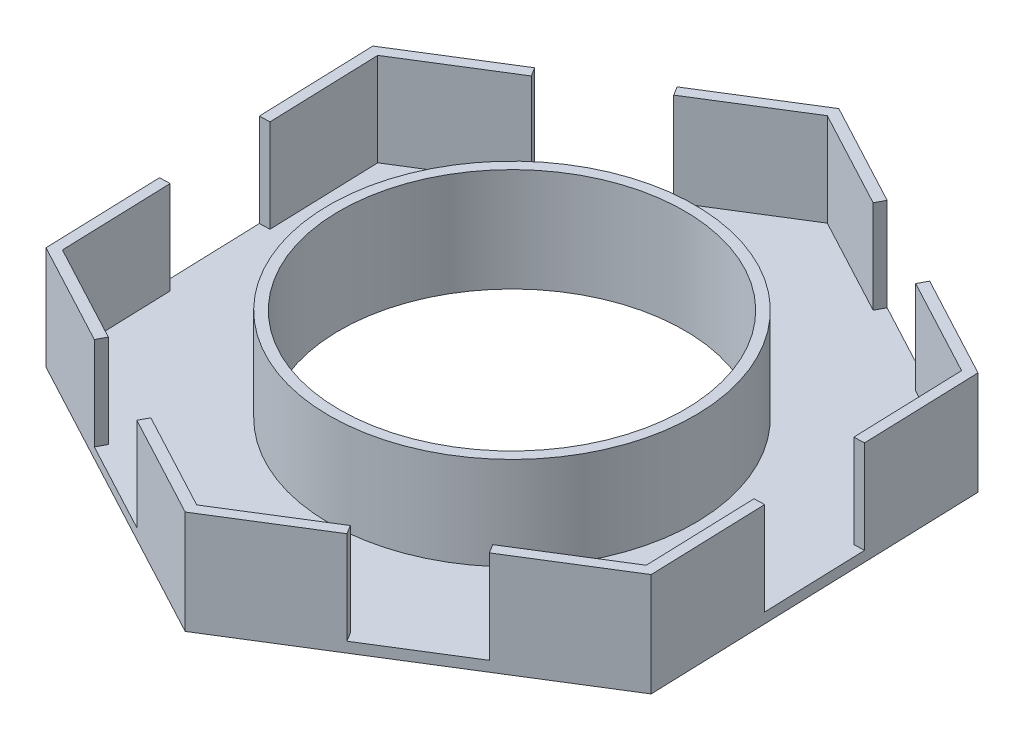
SolidWorks part; units mm, degrees
ref_plane "Front Plane" through (0, 0, 0) normal (0, 0, 1) x (1, 0, 0)
ref_plane "Top Plane" through (0, 0, 0) normal (0, 1, 0) x (1, 0, 0)
ref_plane "Right Plane" through (0, 0, 0) normal (1, 0, 0) x (0, 0, -1)
sketch "Sketch2" plane through (0, 0, 0) normal (0, 1, 0) x (1, 0, 0)
  line L1 (-83.3149, -51.8841) -> (3.2755, -98.0949)
  line L2 (3.2755, -98.0949) -> (86.5904, -46.2108)
  line L3 (86.5904, -46.2108) -> (83.3149, 51.8841)
  line L4 (83.3149, 51.8841) -> (-3.2755, 98.0949)
  line L5 (-3.2755, 98.0949) -> (-86.5904, 46.2108)
  line L6 (-86.5904, 46.2108) -> (-83.3149, -51.8841)
  circle A0 centre (0, 0) radius 50
  circle A1 centre (0, 0) radius 85 construction
extrude "Boss-Extrude1" add sketch "Sketch2" along normal blind 30
shell "Shell1" thickness 3
sketch "Sketch8" plane through (0, 30, 0) normal (0, 1, 0) x (1, 0, 0)
  line L0 (53.2531, 67.9272) -> (51.8407, 65.2805)
  line L1 (83.3149, 51.8841) -> (-3.2755, 98.0949) construction
  line L2 (80.3744, 50.0529) -> (-3.1599, 94.6327) construction
  line L3 (51.8407, 65.2805) -> (25.3738, 79.4051)
  line L4 (25.3738, 79.4051) -> (26.7862, 82.0518)
  line L5 (26.7862, 82.0518) -> (53.2531, 67.9272)
  line L6 (84.4521, 17.8283) -> (85.4532, -12.155)
  line L7 (82.4549, -12.2551) -> (81.4537, 17.7282)
  line L8 (85.4532, -12.155) -> (82.4549, -12.2551)
  line L9 (81.4537, 17.7282) -> (84.4521, 17.8283)
  line L10 (57.6658, -64.2235) -> (32.2001, -80.0822)
  line L11 (30.6142, -77.5356) -> (56.0799, -61.6769)
  line L12 (32.2001, -80.0822) -> (30.6142, -77.5356)
  line L13 (56.0799, -61.6769) -> (57.6658, -64.2235)
  line L14 (-26.7862, -82.0518) -> (-53.2531, -67.9272)
  line L15 (-51.8407, -65.2805) -> (-25.3738, -79.4051)
  line L16 (-53.2531, -67.9272) -> (-51.8407, -65.2805)
  line L17 (-25.3738, -79.4051) -> (-26.7862, -82.0518)
  line L18 (-84.4521, -17.8283) -> (-85.4532, 12.155)
  line L19 (-82.4549, 12.2551) -> (-81.4537, -17.7282)
  line L20 (-85.4532, 12.155) -> (-82.4549, 12.2551)
  line L21 (-81.4537, -17.7282) -> (-84.4521, -17.8283)
  line L22 (-57.6658, 64.2235) -> (-32.2001, 80.0822)
  line L23 (-30.6142, 77.5356) -> (-56.0799, 61.6769)
  line L24 (-32.2001, 80.0822) -> (-30.6142, 77.5356)
  line L25 (-56.0799, 61.6769) -> (-57.6658, 64.2235)
  point P9 (40.0197, 74.9895)
  point P32 (0, 0)
  dimension "D1" = 30
  dimension "D2" = 15
  dimension "D3" = 6
extrude "Cut-Extrude1" cut sketch "Sketch8" against normal blind 27
